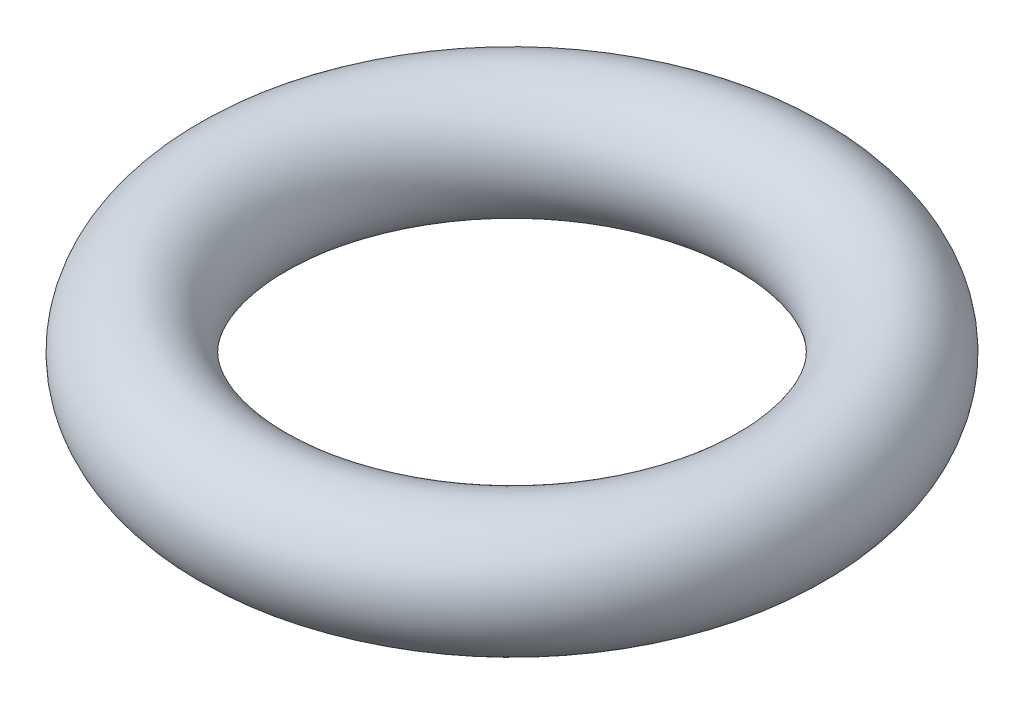
SolidWorks part; units mm, degrees
material "Rubber"
ref_plane "Front Plane" through (0, 0, 0) normal (0, 0, 1) x (1, 0, 0)
ref_plane "Top Plane" through (0, 0, 0) normal (0, 1, 0) x (1, 0, 0)
ref_plane "Right Plane" through (0, 0, 0) normal (1, 0, 0) x (0, 0, -1)
sketch "Sketch1" plane through (0, 0, 0) normal (0, 0, 1) x (1, 0, 0)
  line L0 (0, 24.2788) -> (0, -27.8102) construction
  line L1 (0, 0) -> (1.524, 0) construction
  line L2 (1.524, 0) -> (1.9685, 0) construction
  circle A0 centre (1.9685, 0) radius 0.4445
  dimension "D3" = 0.889
  dimension "D1" = 1.524
  dimension "D2" = 0.4445
revolve "Revolve1" add sketch "Sketch1" angle 360 about L0
